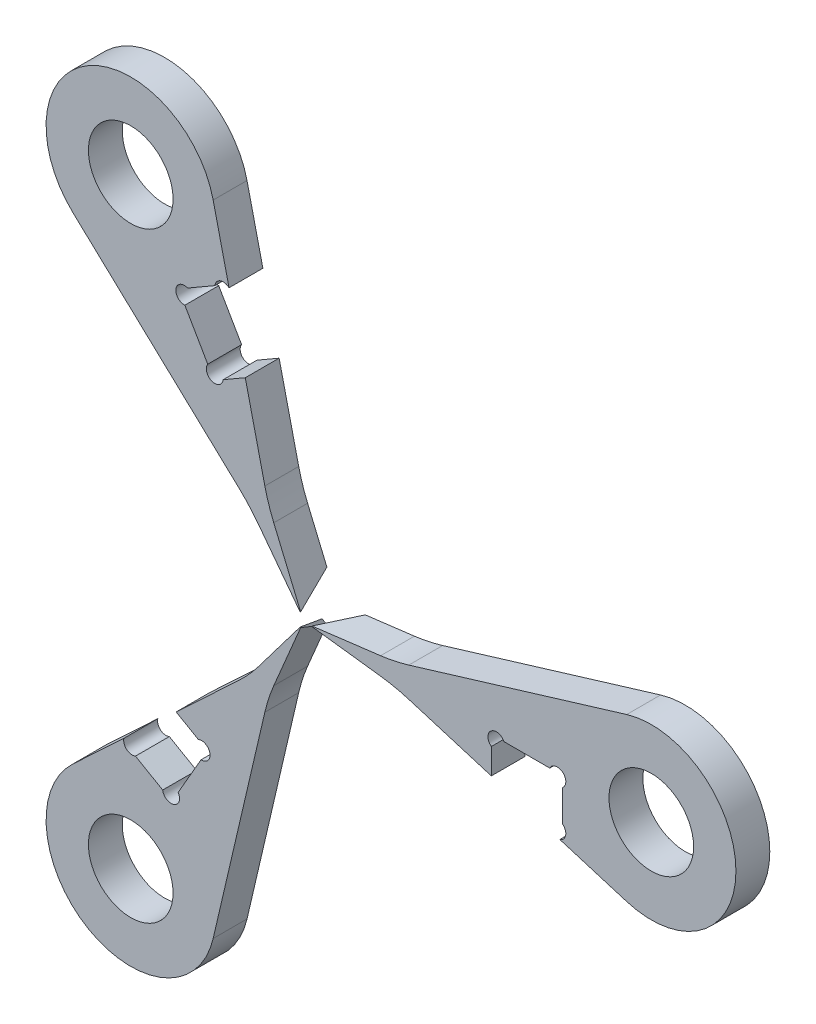
SolidWorks part; units mm, degrees
ref_plane "前基準面" through (0, 0, 0) normal (0, 0, 1) x (1, 0, 0)
ref_plane "上基準面" through (0, 0, 0) normal (0, 1, 0) x (1, 0, 0)
ref_plane "右基準面" through (0, 0, 0) normal (1, 0, 0) x (0, 0, -1)
sketch "草圖1" plane through (0, 0, 0) normal (0, 0, 1) x (1, 0, 0)
  line L0 (0.3574, 0.005) -> (20.1903, 2.4807) construction
  line L1 (20.1903, -2.4807) -> (0.3574, -0.005) construction
  line L2 (0.3574, 0.005) -> (4.5094, 0.5233)
  line L3 (0.3574, -0.005) -> (4.5094, -0.5233)
  line L4 (6.1751, 0.8773) -> (19.0478, 4.7845)
  line L5 (6.1751, -0.8773) -> (19.0478, -4.7845)
  line L6 (-2.3278, -5.7864) -> (-5.3804, -18.8881)
  line L7 (-0.1744, -0.312) -> (-1.8015, -4.1669)
  line L8 (-0.183, -0.307) -> (-2.7079, -3.6436)
  line L9 (-3.8473, -4.9091) -> (-13.6674, -14.1037)
  line L10 (-3.8473, 4.9091) -> (-13.6674, 14.1037)
  line L11 (-0.183, 0.307) -> (-2.7079, 3.6436)
  line L12 (-0.1744, 0.312) -> (-1.8015, 4.1669)
  line L13 (-2.3278, 5.7864) -> (-5.3804, 18.8881)
  circle A0 centre (0, 0) radius 0.353 construction
  arc A1 (0.3574, 0.005) -> (0.3574, -0.005) centre (0.358, 0) ccw
  arc A2 (19.0478, -4.7845) -> (19.0478, 4.7845) centre (20.5, 0) ccw
  circle A3 centre (20.5, 0) radius 2.5
  arc A4 (4.5094, -0.5233) -> (6.1751, -0.8773) centre (3.2707, -10.4463) cw
  arc A5 (4.5094, 0.5233) -> (6.1751, 0.8773) centre (3.2707, 10.4463) ccw
  arc A6 (-13.6674, -14.1037) -> (-5.3804, -18.8881) centre (-10.25, -17.7535) ccw
  arc A7 (-1.8015, -4.1669) -> (-2.3278, -5.7864) centre (7.4114, -8.0556) ccw
  arc A8 (-0.1744, -0.312) -> (-0.183, -0.307) centre (-0.179, -0.31) ccw
  arc A9 (-2.7079, -3.6436) -> (-3.8473, -4.9091) centre (-10.6821, 2.3906) cw
  circle A10 centre (-10.25, -17.7535) radius 2.5
  arc A11 (-5.3804, 18.8881) -> (-13.6674, 14.1037) centre (-10.25, 17.7535) ccw
  arc A12 (-2.7079, 3.6436) -> (-3.8473, 4.9091) centre (-10.6821, -2.3906) ccw
  arc A13 (-0.183, 0.307) -> (-0.1744, 0.312) centre (-0.179, 0.31) ccw
  arc A14 (-1.8015, 4.1669) -> (-2.3278, 5.7864) centre (7.4114, 8.0556) cw
  circle A15 centre (-10.25, 17.7535) radius 2.5
  point P18 (5.3574, -0.6291)
  point P21 (5.3574, 0.6291)
  point P48 (0, 0)
  dimension "D1" = 0.706
  dimension "D2" = 0.01
  dimension "D3" = 10
  dimension "D5" = 5
  dimension "D7" = 10
  dimension "D4" = 20.5
  dimension "D6" = 5
  dimension "D8" = 3
extrude "填料-伸長1" add sketch "草圖1" along normal blind 2
ref_plane "平面1" through (0, 0, 2) normal (0, 0, 1) x (1, 0, 0)
sketch "草圖2" plane through (0, 0, 2) normal (0, 0, 1) x (1, 0, 0)
  line L0 (0, 0) -> (25.5, 0) construction
  line L1 (11.05, -0.2286) -> (15.25, -0.2286)
  line L2 (15.25, -0.2286) -> (15.25, -3.3286)
  line L3 (15.25, -3.3286) -> (11.05, -3.3286)
  line L4 (11.05, -3.3286) -> (11.05, -0.2286)
  line L5 (13.15, -0.2286) -> (13.15, -3.3286) construction
  line L6 (11.05, -1.7786) -> (15.25, -1.7786) construction
  line L7 (13.15, -1.7786) -> (11.05, -0.2286) construction
  line L12 (0, 0) -> (-12.75, 22.0836) construction
  line L13 (-6.575, 11.3882) -> (9.1959, 20.4936) construction
  line L14 (-7.4271, 13.3212) -> (-5.3271, 9.6839)
  line L19 (-7.4271, 13.3212) -> (-4.7424, 14.8712)
  line L20 (-4.7424, 14.8712) -> (-2.6424, 11.2339)
  line L21 (-2.6424, 11.2339) -> (-5.3271, 9.6839)
  line L22 (-6.0847, 14.0962) -> (-3.9847, 10.4589) construction
  line L23 (-4.7424, 14.8712) -> (-5.3271, 9.6839) construction
  line L24 (-7.4271, 13.3212) -> (-2.6424, 11.2339) construction
  line L25 (-4.7841, 14.5007) -> (-3.8841, 12.9418) construction
  line L26 (0, 0) -> (-12.75, -22.0836) construction
  line L27 (-6.575, -11.3882) -> (-31.3313, 2.9048) construction
  line L28 (-5.7229, -9.4553) -> (-7.8229, -13.0926)
  line L29 (-5.7229, -9.4553) -> (-8.4076, -7.9053)
  line L30 (-8.4076, -7.9053) -> (-10.5076, -11.5426)
  line L31 (-10.5076, -11.5426) -> (-7.8229, -13.0926)
  line L32 (-7.0653, -8.6803) -> (-9.1653, -12.3176) construction
  line L33 (-8.4076, -7.9053) -> (-7.8229, -13.0926) construction
  line L34 (-10.5076, -11.5426) -> (-5.7229, -9.4553) construction
  line L35 (-10.1659, -11.3935) -> (-9.2659, -9.8347) construction
  arc A0 (19.0478, -4.7845) -> (19.0478, 4.7845) centre (20.5, 0) ccw construction
  circle A1 centre (11.35, -0.45) radius 0.5
  circle A2 centre (14.95, -0.45) radius 0.5
  circle A3 centre (14.95, -3.1071) radius 0.5
  circle A4 centre (11.35, -3.1071) radius 0.5
  circle A5 centre (13.15, -0.9886) radius 0.15 construction
  circle A6 centre (14, -3.1071) radius 1.05
  arc A9 (-5.3804, 18.8881) -> (-13.6674, 14.1037) centre (-10.25, 17.7535) ccw construction
  circle A15 centre (-7.0853, 13.1721) radius 0.5
  circle A19 centre (-4.7841, 14.5007) radius 0.5
  circle A20 centre (-2.9841, 11.383) radius 0.5
  circle A21 centre (-5.2853, 10.0544) radius 0.5
  circle A22 centre (-4.3091, 13.6779) radius 1.05
  arc A23 (-13.6674, -14.1037) -> (-5.3804, -18.8881) centre (-10.25, -17.7535) ccw construction
  circle A24 centre (-6.0647, -9.6044) radius 0.5
  circle A25 centre (-7.8647, -12.7221) radius 0.5
  circle A26 centre (-8.3659, -8.2758) radius 0.5
  circle A27 centre (-10.1659, -11.3935) radius 0.5
  circle A28 centre (-9.6909, -10.5708) radius 1.05
  point P35 (-6.3771, 11.5025)
  point P59 (-6.7729, -11.2739)
  dimension "D3" = 1
  dimension "D4" = 0.3
  dimension "D7" = 2.1
  dimension "D10" = 13.15
  dimension "D13" = 1
  dimension "D16" = 2.1
  dimension "D21" = 1
  dimension "D24" = 2.1
  dimension "D26" = 0.3
  dimension "D1" = 4.2
  dimension "D2" = 3.1
  dimension "D5" = 0.79
  dimension "D6" = 0.45
  dimension "D8" = 1.25
  dimension "D9" = 13.15
  dimension "D11" = 4.2
  dimension "D12" = 3.1
  dimension "D14" = 0.3
  dimension "D15" = 0.45
  dimension "D17" = 1.25
  dimension "D18" = 13.15
  dimension "D19" = 4.2
  dimension "D20" = 3.1
  dimension "D22" = 0.3
  dimension "D23" = 0.45
  dimension "D25" = 1.25
extrude "除料-伸長1" cut sketch "草圖2" against normal through all
sketch "草圖3" plane through (0, 0, 0) normal (0, 1, 0) x (1, 0, 0)
  line L0 (0, 4.2459) -> (0, -4.225) construction
  line L1 (0.353, -2.18) -> (1.6116, 0)
  line L3 (0.353, 0) -> (0.353, -2) construction
  line L4 (4.5094, 0) -> (0.3574, 0) construction
  line L5 (1.6116, 0) -> (0.353, 0)
  line L6 (0.353, 0) -> (0.353, -2.18)
  line L7 (-5.5, -2) -> (5.5, -2) construction
  dimension "D1" = 0.18
  dimension "D2" = 30
revolve "除料-旋轉1" cut sketch "草圖3" angle 360 about L0
